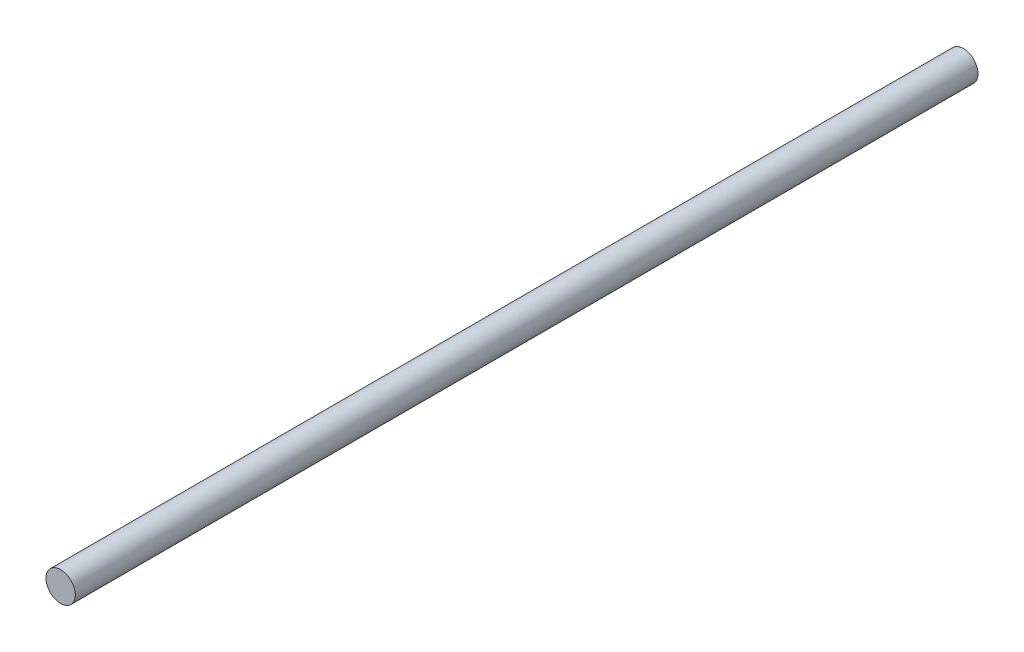
SolidWorks part; units mm, degrees
ref_plane "Front Plane" through (0, 0, 0) normal (0, 0, 1) x (1, 0, 0)
ref_plane "Top Plane" through (0, 0, 0) normal (0, 1, 0) x (1, 0, 0)
ref_plane "Right Plane" through (0, 0, 0) normal (1, 0, 0) x (0, 0, -1)
sketch "Sketch1" plane through (0, 0, 0) normal (0, 0, 1) x (1, 0, 0)
  circle A0 centre (3.9472, -0.7687) radius 3.25
  dimension "D1" = 6.5
extrude "Boss-Extrude1" add sketch "Sketch1" along normal blind 200
